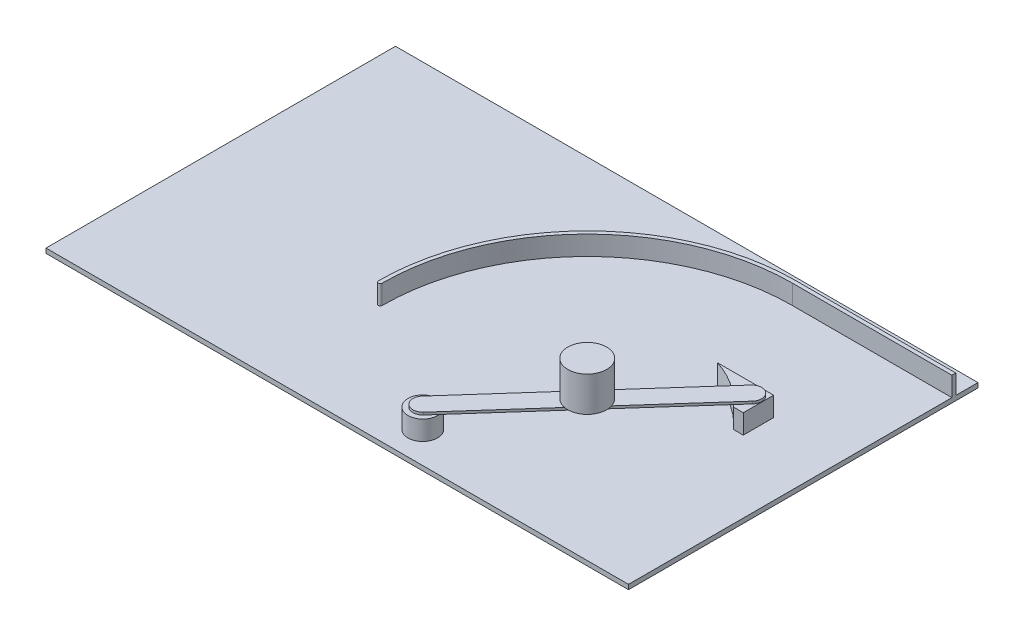
SolidWorks part; units mm, degrees
ref_plane "Front Plane" through (0, 0, 0) normal (0, 0, 1) x (1, 0, 0)
ref_plane "Top Plane" through (0, 0, 0) normal (0, 1, 0) x (1, 0, 0)
ref_plane "Right Plane" through (0, 0, 0) normal (1, 0, 0) x (0, 0, -1)
sketch "Sketch1" plane through (0, 0, 0) normal (0, 1, 0) x (1, 0, 0)
  line L1 (750, -450) -> (-750, -450)
  line L2 (750, -450) -> (750, 450)
  line L3 (750, 450) -> (-750, 450)
  line L4 (-750, -450) -> (-750, 450)
  line L5 (750, -450) -> (-750, 450) construction
  line L6 (750, 450) -> (-750, -450) construction
  point P0 (0, 0)
  dimension "D1" = 900
  dimension "D2" = 1500
extrude "Boss-Extrude1" add sketch "Sketch1" along normal blind 12
sketch "Sketch2" plane through (0, 12, 0) normal (0, 1, 0) x (1, 0, 0)
  line L0 (-750, -450) -> (750, -450) construction
  line L1 (339, 382.8) -> (750, 382.8)
  line L4 (750, -450) -> (750, 450) construction
  line L5 (339, 392.8) -> (750, 392.8)
  line L6 (750, 392.8) -> (750, 382.8)
  circle A0 centre (339, -145.2) radius 254
  arc A1 (339, 382.8) -> (-189, -145.2) centre (339, -145.2) ccw
  arc A2 (339, 392.8) -> (-199, -145.2) centre (339, -145.2) ccw
  arc A4 (-189, -145.2) -> (-199, -145.2) centre (-194, -145.2) cw
  point P7 (339, -145.2)
  dimension "D1" = 508
  dimension "D2" = 304.8
  dimension "D3" = 274
  dimension "D4" = 411
  dimension "D5" = 10
extrude "Boss-Extrude2" add sketch "Sketch2" along normal blind 50 contours A1 A4 A2 L5 L6 L1
sketch "Sketch3" plane through (0, 12, 0) normal (0, 1, 0) x (1, 0, 0)
  line L1 (564.9915, 108.8) -> (420.3197, 108.8)
  line L2 (564.9915, 108.8) -> (564.9915, 30.561)
  line L3 (564.9915, 30.561) -> (539.5915, 30.561)
  arc A0 (420.3197, 108.8) -> (539.5915, 30.561) centre (339, -145.2) cw
  circle A1 centre (339, -145.2) radius 254 construction
  dimension "D1" = 12.7
  dimension "D2" = 25.4
  dimension "D3" = 78.239
extrude "Boss-Extrude3" add sketch "Sketch3" along normal blind 50
sketch "Sketch4" plane through (0, 62, 0) normal (0, 1, 0) x (1, 0, 0)
  line L0 (139.5855, -369.3291) -> (538.4145, 78.9291) construction
  line L1 (120.6093, -352.4454) -> (519.4382, 95.8129)
  line L2 (158.5618, -386.2129) -> (557.3907, 62.0454)
  line L3 (538.4145, 78.9291) -> (639.0151, 191.9978) construction
  arc A1 (120.6093, -352.4454) -> (158.5618, -386.2129) centre (139.5855, -369.3291) ccw
  arc A2 (557.3907, 62.0454) -> (519.4382, 95.8129) centre (538.4145, 78.9291) ccw
  point P2 (339, -145.2)
  point P4 (339, -145.2)
  point P9 (139.5855, -369.3291)
  point P12 (111.2845, -344.1489)
  dimension "D1" = 600
  dimension "D2" = 50.8
extrude "Boss-Extrude4" add sketch "Sketch4" along normal blind 6.35
sketch "Sketch5" plane through (0, 12, 0) normal (0, 1, 0) x (1, 0, 0)
  circle A0 centre (139.5855, -369.3291) radius 38.1
  dimension "D1" = 76.2
extrude "Boss-Extrude5" add sketch "Sketch5" along normal up to surface (50 mm away) up to face at (323.5101, 62, 162.6097)
sketch "Sketch6" plane through (0, 68.35, 0) normal (0, 1, 0) x (1, 0, 0)
  circle A0 centre (339, -145.2) radius 50
  dimension "D1" = 100
extrude "Boss-Extrude6" add sketch "Sketch6" along normal blind 90
equation "\"D2@Sketch2\"=\"D1@Sketch2\"/2+2*25.4"
